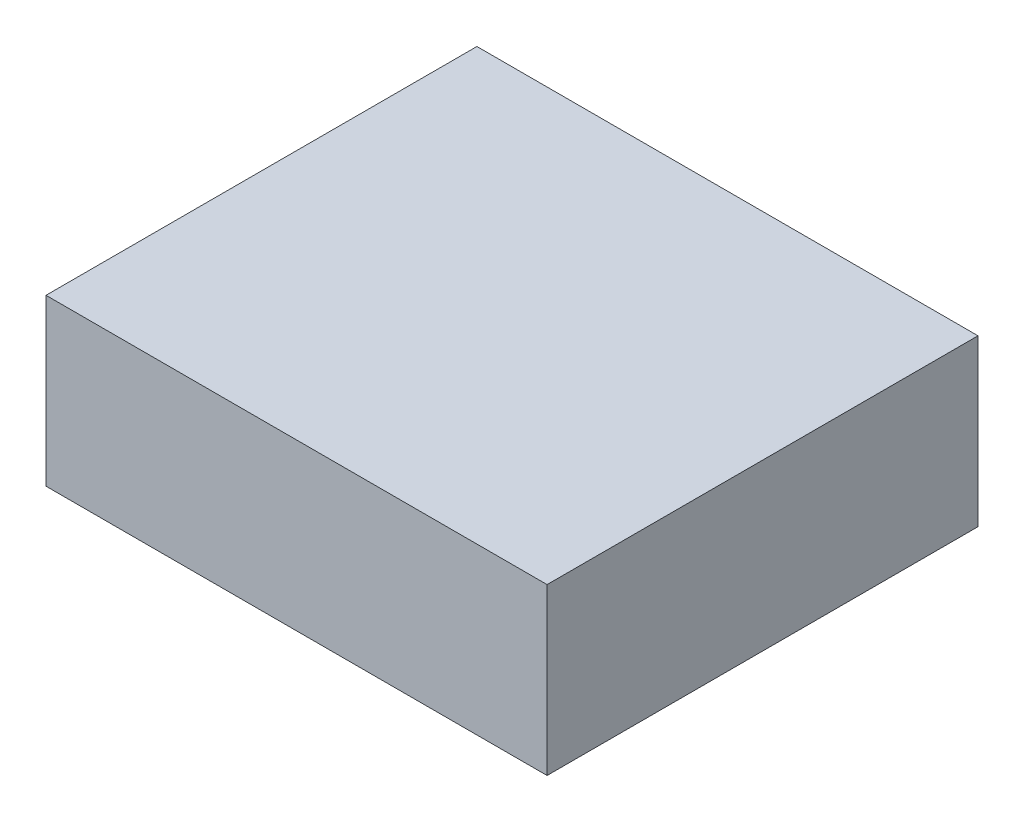
SolidWorks part; units mm, degrees
ref_plane "前视基准面" through (0, 0, 0) normal (0, 0, 1) x (1, 0, 0)
ref_plane "上视基准面" through (0, 0, 0) normal (0, 1, 0) x (1, 0, 0)
ref_plane "右视基准面" through (0, 0, 0) normal (1, 0, 0) x (0, 0, -1)
other "Configuration Table"
sketch "草图1" plane through (0, 0, 0) normal (0, 1, 0) x (1, 0, 0)
  line L1 (0, 0) -> (100, 0)
  line L2 (0, 0) -> (0, -86)
  line L3 (0, -86) -> (100, -86)
  line L4 (100, 0) -> (100, -86)
  dimension "D1" = 86
  dimension "D2" = 100
extrude "凸台-拉伸1" add sketch "草图1" along normal blind 33
